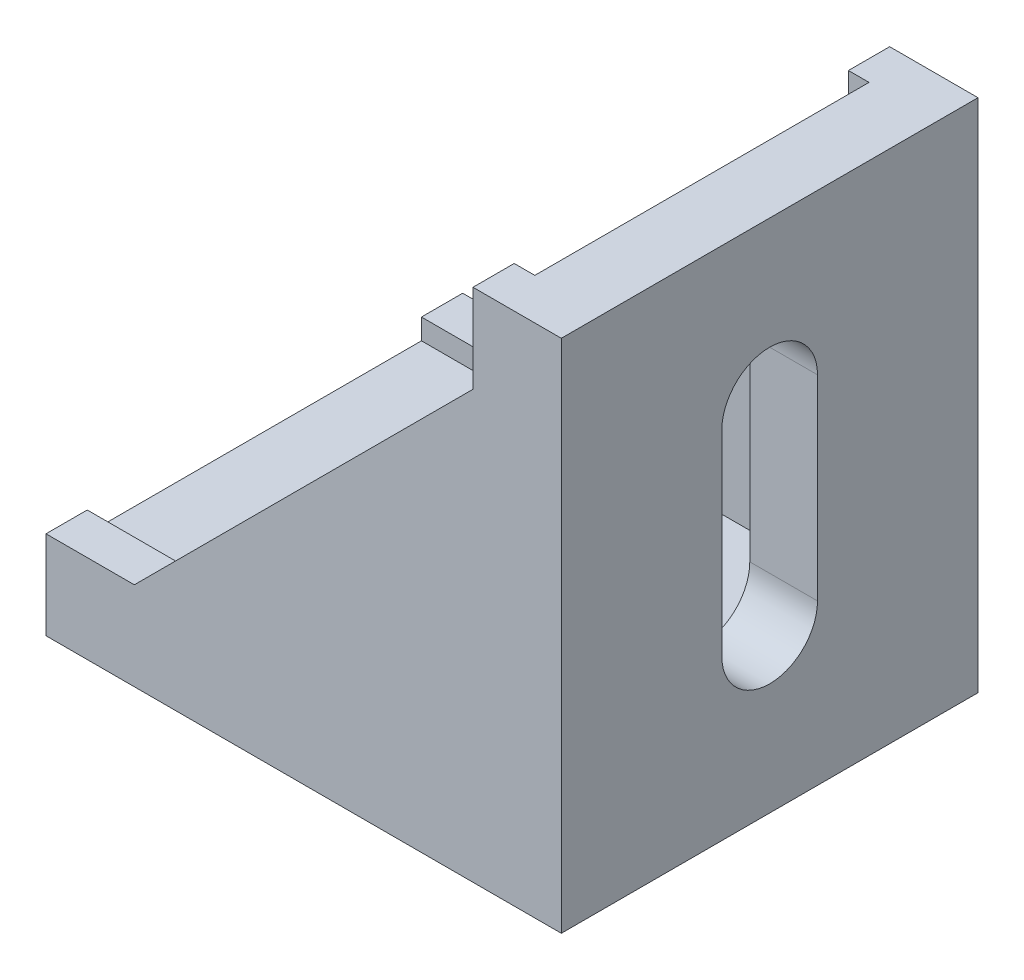
SolidWorks part; units mm, degrees
ref_plane "前视基准面" through (0, 0, 0) normal (0, 0, 1) x (1, 0, 0)
ref_plane "上视基准面" through (0, 0, 0) normal (0, 1, 0) x (1, 0, 0)
ref_plane "右视基准面" through (0, 0, 0) normal (1, 0, 0) x (0, 0, -1)
other "Configuration Table"
sketch "草图1" plane through (0, 0, 0) normal (0, 0, 1) x (1, 0, 0)
  line L0 (0, 0) -> (35, 0)
  line L1 (35, 0) -> (35, 35)
  line L2 (35, 35) -> (29, 35)
  line L3 (29, 35) -> (29, 29)
  line L4 (29, 29) -> (6, 6)
  line L5 (6, 6) -> (0, 6)
  line L6 (0, 6) -> (0, 0)
  dimension "D1" = 35
  dimension "D2" = 6
  dimension "D3" = 6
extrude "凸台-拉伸1" add sketch "草图1" along normal mid plane 28.3
sketch "草图2" plane through (0, 0, 0) normal (0, 0, 1) x (1, 0, 0)
  line L0 (0, 4.6) -> (30.4, 4.6)
  line L1 (0, 6) -> (0, 0) construction
  line L2 (30.4, 4.6) -> (30.4, 35)
  line L3 (35, 35) -> (29, 35) construction
  line L4 (30.4, 35) -> (0, 35)
  line L5 (0, 35) -> (0, 4.6)
  line L6 (35, 0) -> (35, 35) construction
  dimension "D1" = 4.6
extrude "切除-拉伸1" cut sketch "草图2" along normal mid plane 22.7
sketch "草图4" plane through (0, 0, 0) normal (0, 1, 0) x (1, 0, 0)
  line L0 (10.85, 0) -> (24.15, 0) construction
  line L1 (10.85, 3.25) -> (24.15, 3.25)
  line L2 (10.85, -3.25) -> (24.15, -3.25)
  arc A0 (10.85, 3.25) -> (10.85, -3.25) centre (10.85, 0) ccw
  arc A1 (24.15, -3.25) -> (24.15, 3.25) centre (24.15, 0) ccw
  point P3 (17.5, 0)
  dimension "D1" = 6.5
  dimension "D2" = 13.3
  dimension "D3" = 17.5
extrude "切除-拉伸2" cut sketch "草图4" along normal up to next
sketch "草图5" plane through (0, 0, 0) normal (1, 0, 0) x (0, 0, -1)
  line L0 (0, 10.85) -> (0, 24.15) construction
  line L1 (-3.25, 10.85) -> (-3.25, 24.15)
  line L2 (3.25, 10.85) -> (3.25, 24.15)
  arc A0 (-3.25, 10.85) -> (3.25, 10.85) centre (0, 10.85) ccw
  arc A1 (3.25, 24.15) -> (-3.25, 24.15) centre (0, 24.15) ccw
  point P3 (0, 17.5)
  dimension "D1" = 6.5
  dimension "D2" = 17.5
  dimension "D3" = 13.3
extrude "切除-拉伸3" cut sketch "草图5" along normal up to next
